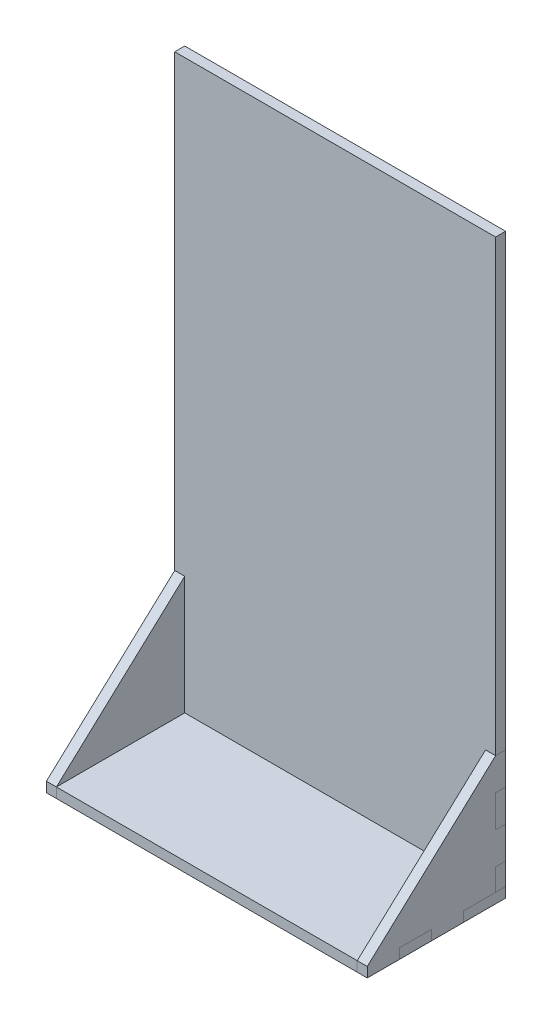
SolidWorks part; units mm, degrees
ref_plane "Front Plane" through (0, 0, 0) normal (0, 0, 1) x (1, 0, 0)
ref_plane "Top Plane" through (0, 0, 0) normal (0, 1, 0) x (1, 0, 0)
ref_plane "Right Plane" through (0, 0, 0) normal (1, 0, 0) x (0, 0, -1)
sketch "Sketch1" plane through (0, 0, 0) normal (0, 0, 1) x (1, 0, 0)
  line L0 (0, 0) -> (10, 0)
  line L1 (10, 0) -> (10, 3.12)
  line L2 (0, 0) -> (0, 10)
  line L3 (0, 180) -> (100, 180)
  line L4 (100, 3.12) -> (100, 10)
  line L5 (10, 3.12) -> (20, 3.12)
  line L6 (20, 3.12) -> (20, 0)
  line L7 (20, 0) -> (30, 0)
  line L8 (30, 0) -> (30, 3.12)
  line L9 (30, 3.12) -> (40, 3.12)
  line L10 (40, 3.12) -> (40, 0)
  line L11 (40, 0) -> (50, 0)
  line L12 (50, 0) -> (50, 3.12)
  line L13 (50, 3.12) -> (60, 3.12)
  line L14 (60, 3.12) -> (60, 0)
  line L15 (60, 0) -> (70, 0)
  line L16 (70, 0) -> (70, 3.12)
  line L17 (70, 3.12) -> (80, 3.12)
  line L18 (80, 3.12) -> (80, 0)
  line L19 (80, 0) -> (90, 0)
  line L20 (90, 0) -> (90, 3.12)
  line L21 (90, 3.12) -> (100, 3.12)
  line L22 (3.12, 10) -> (0, 10)
  line L23 (3.12, 10) -> (3.12, 20)
  line L24 (3.12, 20) -> (0, 20)
  line L25 (0, 30) -> (3.12, 30)
  line L26 (3.12, 30) -> (3.12, 40)
  line L27 (3.12, 40) -> (0, 40)
  line L28 (0, 20) -> (0, 30)
  line L29 (0, 40) -> (0, 180)
  line L30 (50, 180) -> (50, 40) construction
  line L31 (96.88, 10) -> (96.88, 20)
  line L32 (96.88, 40) -> (100, 40)
  line L33 (96.88, 30) -> (96.88, 40)
  line L34 (100, 30) -> (96.88, 30)
  line L35 (96.88, 20) -> (100, 20)
  line L36 (96.88, 10) -> (100, 10)
  line L37 (100, 40) -> (100, 180)
  line L38 (100, 20) -> (100, 30)
  dimension "D1" = 180
  dimension "D2" = 10
  dimension "D3" = 10
  dimension "D4" = 10
  dimension "D5" = 3.12
  dimension "D6" = 3.12
  dimension "D7" = 10
  dimension "D8" = 10
extrude "Boss-Extrude1" add sketch "Sketch1" along normal blind 3.12
ref_plane "Plane1" through (50, 0, 0) normal (-1, 0, 0) x (0, 0, 1)
sketch "Sketch2" plane through (0, 0, 0) normal (0, -1, 0) x (1, 0, 0)
  line L0 (10, 3.12) -> (10, 0)
  line L1 (0, 3.12) -> (10, 3.12)
  line L2 (0, 3.12) -> (0, 13.12)
  line L3 (3.12, 43.12) -> (96.88, 43.12)
  line L4 (3.12, 23.12) -> (96.88, 23.12) construction
  line L5 (10, 0) -> (20, 0)
  line L6 (20, 0) -> (20, 3.12)
  line L7 (30, 3.12) -> (30, 0)
  line L8 (30, 0) -> (40, 0)
  line L9 (40, 0) -> (40, 3.12)
  line L10 (50, 3.12) -> (50, 0)
  line L11 (50, 0) -> (60, 0)
  line L12 (60, 0) -> (60, 3.12)
  line L13 (70, 3.12) -> (70, 0)
  line L14 (70, 0) -> (80, 0)
  line L15 (80, 0) -> (80, 3.12)
  line L16 (90, 3.12) -> (90, 0)
  line L17 (90, 0) -> (100, 0)
  line L18 (100, 0) -> (100, 3.12)
  line L19 (60, 3.12) -> (70, 3.12)
  line L20 (80, 3.12) -> (90, 3.12)
  line L21 (20, 3.12) -> (30, 3.12)
  line L22 (40, 3.12) -> (50, 3.12)
  line L23 (0, 13.12) -> (3.12, 13.12)
  line L24 (3.12, 13.12) -> (3.12, 23.12)
  line L25 (3.12, 23.12) -> (0, 23.12)
  line L26 (0, 23.12) -> (0, 33.12)
  line L27 (0, 33.12) -> (3.12, 33.12)
  line L28 (3.12, 33.12) -> (3.12, 43.12)
  line L29 (50, 42.0795) -> (50, 3.12) construction
  line L30 (96.88, 33.12) -> (96.88, 43.12)
  line L31 (100, 33.12) -> (96.88, 33.12)
  line L32 (100, 23.12) -> (100, 33.12)
  line L33 (96.88, 23.12) -> (100, 23.12)
  line L34 (96.88, 13.12) -> (96.88, 23.12)
  line L35 (100, 13.12) -> (96.88, 13.12)
  line L36 (100, 3.12) -> (100, 13.12)
  dimension "D1" = 10
  dimension "D2" = 10
  dimension "D3" = 3.12
  dimension "D4" = 10
extrude "Boss-Extrude2" add sketch "Sketch2" against normal blind 3.12 separate body
sketch "Sketch3" plane through (0, 0, 0) normal (-1, 0, 0) x (0, 0, 1)
  line L0 (3.12, 40) -> (0, 40)
  line L1 (0, 40) -> (0, 30)
  line L2 (0, 30) -> (3.12, 30)
  line L3 (3.12, 30) -> (3.12, 20)
  line L4 (3.12, 20) -> (0, 20)
  line L5 (0, 20) -> (0, 10)
  line L6 (0, 10) -> (3.12, 10)
  line L7 (3.12, 10) -> (0, 10) construction
  line L8 (3.12, 10) -> (3.12, 3.12)
  line L9 (3.12, 3.12) -> (13.12, 3.12)
  line L10 (13.12, 3.12) -> (13.12, 0)
  line L11 (13.12, 0) -> (23.12, 0)
  line L12 (23.12, 0) -> (23.12, 3.12)
  line L13 (23.12, 3.12) -> (23.12, 0) construction
  line L14 (23.12, 3.12) -> (33.12, 3.12)
  line L15 (33.12, 3.12) -> (33.12, 0)
  line L16 (33.12, 0) -> (43.12, 0)
  line L17 (43.12, 0) -> (43.12, 3.12)
  line L18 (43.12, 3.12) -> (3.12, 40)
extrude "Boss-Extrude3" add sketch "Sketch3" against normal blind 3.12 separate body
mirror "Mirror1" about plane through (50, 0, 0) normal (-1, 0, 0) of bodies 103
other "Save Bodies1"
